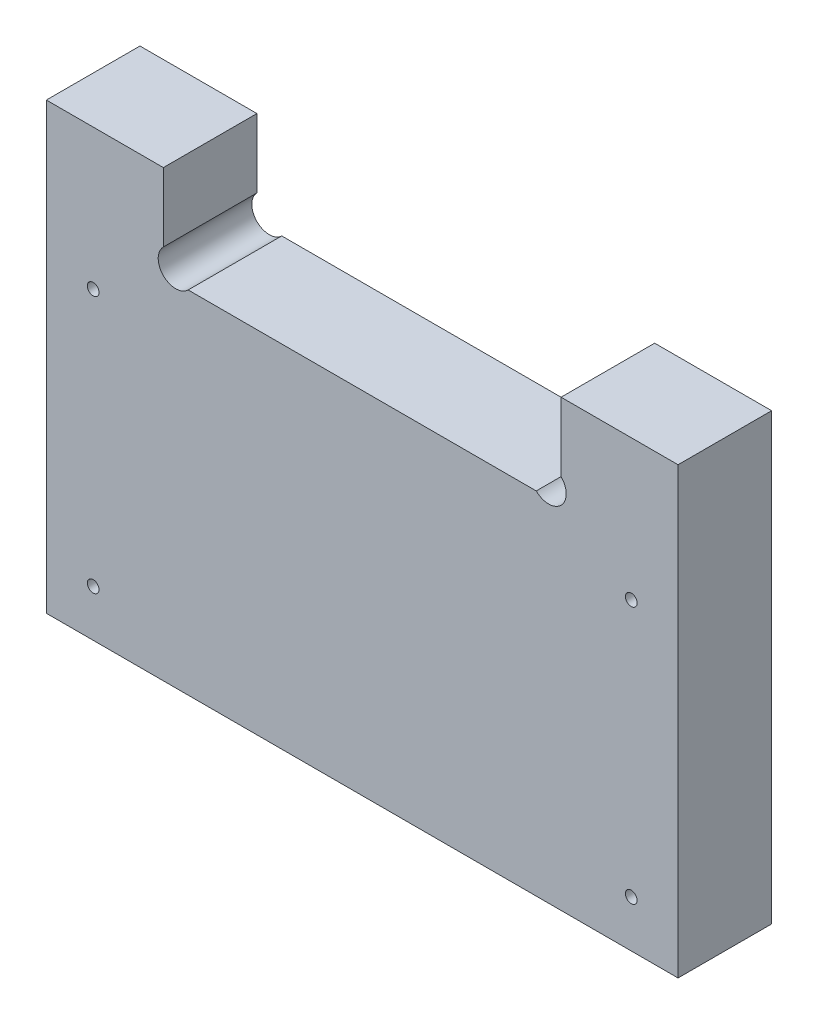
SolidWorks part; units mm, degrees
ref_plane "Plan de face" through (0, 0, 0) normal (0, 0, 1) x (1, 0, 0)
ref_plane "Plan de dessus" through (0, 0, 0) normal (0, 1, 0) x (1, 0, 0)
ref_plane "Plan de droite" through (0, 0, 0) normal (1, 0, 0) x (0, 0, -1)
sketch "Esquisse1" plane through (0, 0, 0) normal (0, 0, 1) x (1, 0, 0)
  line L0 (-114.8269, -6.3478) -> (-114.8269, -44.3478)
  line L1 (-102.7056, -14.3478) -> (-72.9483, -14.3478)
  line L2 (-60.8269, -6.3478) -> (-60.8269, -44.3478)
  line L3 (-114.8269, -44.3478) -> (-60.8269, -44.3478)
  line L5 (-114.8269, -6.3478) -> (-104.8269, -6.3478)
  line L6 (-104.8269, -6.3478) -> (-104.8269, -12.2265)
  line L8 (-60.8269, -6.3478) -> (-70.8269, -6.3478)
  line L9 (-70.8269, -6.3478) -> (-70.8269, -12.2265)
  arc A0 (-104.8269, -12.2265) -> (-102.7056, -14.3478) centre (-103.7663, -13.2872) ccw
  arc A1 (-72.9483, -14.3478) -> (-70.8269, -12.2265) centre (-71.8876, -13.2872) ccw
extrude "Boss.-Extru.1" add sketch "Esquisse1" along normal blind 8
sketch "Esquisse2" plane through (0, 0, 8) normal (0, 0, 1) x (1, 0, 0)
  line L0 (-114.8269, -6.3478) -> (-114.8269, -44.3478) construction
  line L1 (-110.8269, -18.3478) -> (-64.8269, -18.3478) construction
  line L2 (-110.8269, -18.3478) -> (-110.8269, -40.3478) construction
  line L3 (-110.8269, -40.3478) -> (-64.8269, -40.3478) construction
  line L4 (-64.8269, -18.3478) -> (-64.8269, -40.3478) construction
  line L5 (-72.9483, -14.3478) -> (-102.7056, -14.3478) construction
  line L6 (-60.8269, -44.3478) -> (-60.8269, -6.3478) construction
  line L7 (-114.8269, -44.3478) -> (-60.8269, -44.3478) construction
  circle A0 centre (-110.8269, -18.3478) radius 0.5
  circle A1 centre (-64.8269, -18.3478) radius 0.5
  circle A2 centre (-64.8269, -40.3478) radius 0.5
  circle A3 centre (-110.8269, -40.3478) radius 0.5
  point P4 (-114.8269, -25.3478)
  dimension "D1" = 4
  dimension "D2" = 4
  dimension "D3" = 4
  dimension "D4" = 4
extrude "Enlèv. mat.-Extru.1" cut sketch "Esquisse2" against normal blind 8
